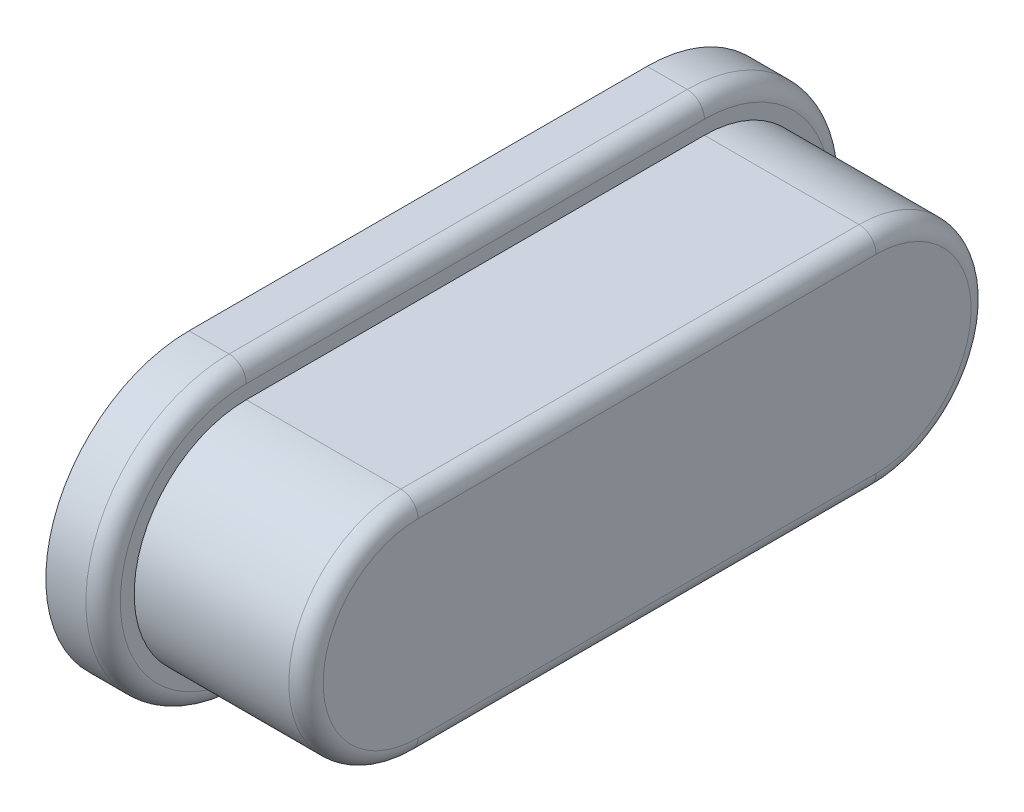
SolidWorks part; units mm, degrees
ref_plane "前视基准面" through (0, 0, 0) normal (0, 0, 1) x (1, 0, 0)
ref_plane "上视基准面" through (0, 0, 0) normal (0, 1, 0) x (1, 0, 0)
ref_plane "右视基准面" through (0, 0, 0) normal (1, 0, 0) x (0, 0, -1)
sketch "草图1" plane through (0, 0, 0) normal (1, 0, 0) x (0, 0, -1)
  line L0 (0, 0) -> (8, 0) construction
  line L1 (0, 2.5) -> (8, 2.5)
  line L2 (0, -2.5) -> (8, -2.5)
  arc A0 (0, 2.5) -> (0, -2.5) centre (0, 0) ccw
  arc A1 (8, -2.5) -> (8, 2.5) centre (8, 0) ccw
  point P3 (4, 0)
  dimension "D1" = 8
extrude "凸台-拉伸1" add sketch "草图1" along normal blind 1
sketch "草图2" plane through (1, 0, 0) normal (1, 0, 0) x (0, 0, -1)
  line L0 (0, 0) -> (8, 0) construction
  line L1 (0, 1.9571) -> (8, 1.9571)
  line L2 (0, -1.9571) -> (8, -1.9571)
  arc A0 (0, 1.9571) -> (0, -1.9571) centre (0, 0) ccw
  arc A1 (8, -1.9571) -> (8, 1.9571) centre (8, 0) ccw
  point P3 (4, 0)
  dimension "D1" = 8
extrude "凸台-拉伸2" add sketch "草图2" along normal blind 3
fillet "圆角1" radius 0.3 8 edges at (4, 0, 1.9571) (4, 1.9571, -4) (4, 0, -9.9571) (4, -1.9571, -4) (1, 2.5, -4) (1, 0, -10.5) (1, 0, 2.5) (1, -2.5, -4)
